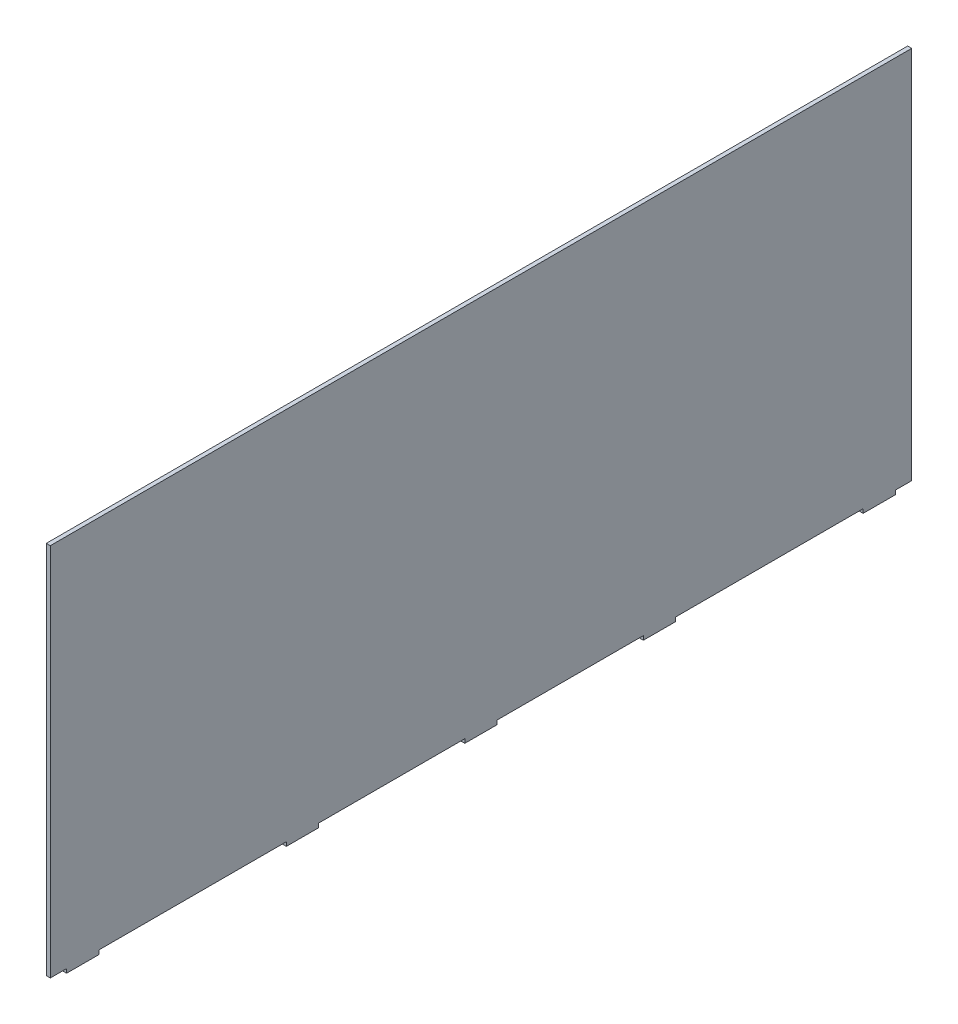
SolidWorks part; units mm, degrees
material "6061-T6 (SS)"
ref_plane "X-Y Datum" through (0, 0, 0) normal (0, 0, 1) x (1, 0, 0)
ref_plane "X-Z Datum" through (0, 0, 0) normal (0, 1, 0) x (1, 0, 0)
ref_plane "Y-Z Datum" through (0, 0, 0) normal (1, 0, 0) x (0, 0, -1)
sketch "Sketch1" plane through (0, 0, 0) normal (1, 0, 0) x (0, 0, -1)
  line L0 (12.7, -145.415) -> (-12.7, -145.415)
  line L1 (-338.201, 148.59) -> (338.201, 148.59)
  line L2 (-338.201, 148.59) -> (-338.201, -148.59)
  line L3 (-338.201, -148.59) -> (338.201, -148.59)
  line L4 (338.201, 148.59) -> (338.201, -148.59)
  line L5 (-338.201, 148.59) -> (338.201, -148.59) construction
  line L6 (-338.201, -148.59) -> (338.201, 148.59) construction
  line L7 (-12.7, -145.415) -> (-12.7, -148.59)
  line L8 (12.7, -145.415) -> (12.7, -148.59)
  line L9 (12.7, -145.415) -> (300.0426, -145.415)
  line L10 (-12.7, -145.415) -> (-12.7, -148.59)
  line L11 (12.7, -145.415) -> (12.7, -148.59)
  line L12 (300.0426, -145.415) -> (300.0426, -148.59)
  line L13 (300.0426, -145.415) -> (325.4426, -145.415) construction
  line L14 (325.4426, -145.415) -> (325.4426, -148.59)
  line L15 (0, 57.4106) -> (0, -57.4106) construction
  line L16 (-325.4426, -145.415) -> (-325.4426, -148.59)
  line L17 (325.4426, -145.415) -> (338.201, -145.415)
  line L18 (-300.0426, -145.415) -> (-300.0426, -148.59)
  line L19 (-12.7, -145.415) -> (-12.7, -148.59)
  line L20 (12.7, -145.415) -> (-12.7, -145.415)
  line L21 (12.7, -145.415) -> (12.7, -148.59)
  line L22 (-338.201, -145.415) -> (-325.4426, -145.415)
  line L24 (152.8724, -145.415) -> (152.8724, -148.59) construction
  line L25 (-300.0426, -145.415) -> (-12.7, -145.415)
  line L26 (127.4724, -145.415) -> (127.4724, -148.59) construction
  line L27 (152.8724, -145.415) -> (152.8724, -148.59)
  line L28 (127.4724, -145.415) -> (127.4724, -148.59)
  line L29 (-152.8724, -145.415) -> (-152.8724, -148.59)
  line L30 (-127.4724, -145.415) -> (-127.4724, -148.59)
  point P0 (0, 0)
  point P9 (0, -74.6125)
  point P22 (0, 0)
  dimension "D1" = 676.402
  dimension "D2" = 294.005
  dimension "D3" = 3.175
  dimension "D4" = 25.4
  dimension "D5" = 2
  dimension "D6" = 2
extrude "Boss-Extrude1" add sketch "Sketch1" along normal blind 3.175 contours L18 L25 L0 L9 L12 L3 L14 L17 L4 L1 L2 L22 L16 | L8 L0 L7 L3 | L30 L25 L29 L3 | L9 L28 L3 L27
